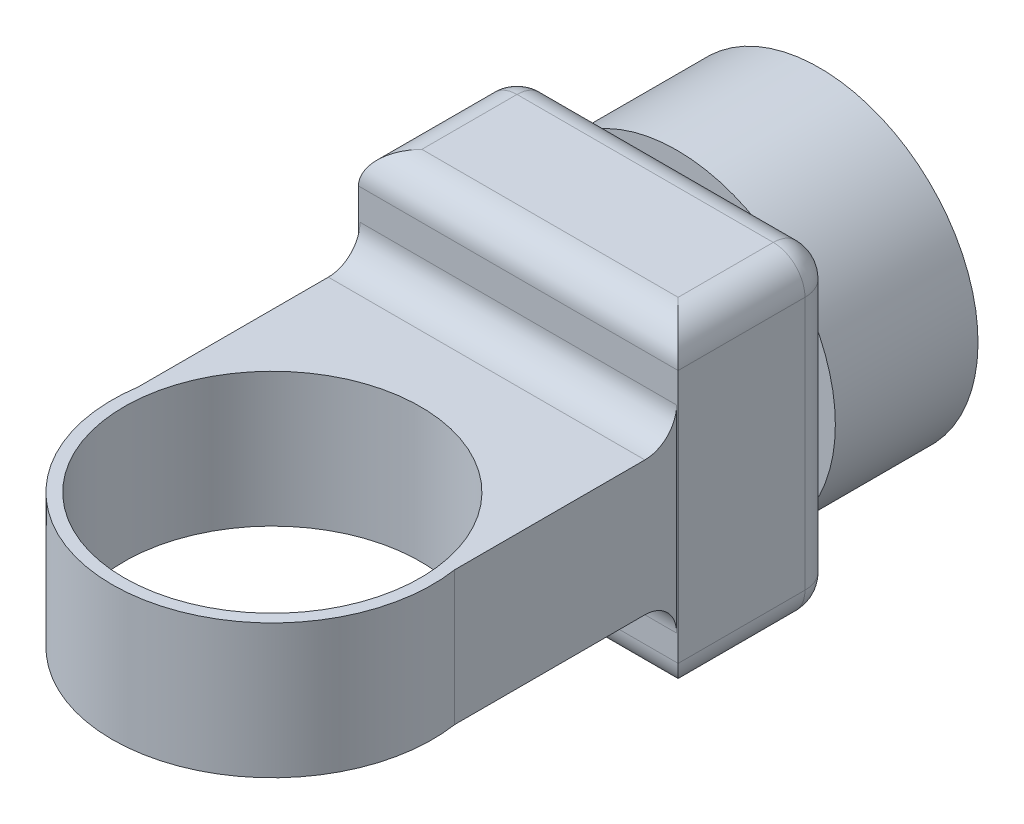
SolidWorks part; units mm, degrees
ref_plane "前视基准面" through (0, 0, 0) normal (0, 0, 1) x (1, 0, 0)
ref_plane "上视基准面" through (0, 0, 0) normal (0, 1, 0) x (1, 0, 0)
ref_plane "右视基准面" through (0, 0, 0) normal (1, 0, 0) x (0, 0, -1)
other "Configuration Table"
sketch "草图1" plane through (0, 0, 0) normal (0, 1, 0) x (1, 0, 0)
  circle A0 centre (0, 0) radius 46.75
  circle A1 centre (0, 0) radius 50.5
  dimension "D1" = 93.5
  dimension "D2" = 101
extrude "凸台-拉伸1" add sketch "草图1" along normal blind 42.3
sketch "草图2" plane through (0, 42.3, 0) normal (0, 1, 0) x (1, 0, 0)
  line L1 (-49.9227, 77.5842) -> (49.9273, 77.5842)
  line L2 (-49.9227, 77.5842) -> (-49.9227, 7.5842)
  line L4 (49.9273, 77.5842) -> (49.9273, 7.5842)
  line L5 (-38.2569, 57.9924) -> (0.0023, 30.5974) construction
  line L6 (-49.9227, 7.5842) -> (0.0023, 30.5974) construction
  circle A0 centre (0, 0) radius 50.5 construction
  arc A4 (-49.9227, 7.5842) -> (49.9273, 7.5842) centre (0.0023, -0.9836) cw
  point P0 (0.0023, 30.5974)
  point P5 (0.0023, 30.5974)
  point P8 (0, 0)
  point P10 (0, 0)
  dimension "D1" = 99.85
  dimension "D2" = 70
  dimension "D3" = 70
extrude "凸台-拉伸3" add sketch "草图2" against normal blind 42.3
sketch "草图10" plane through (0, 0, -77.5842) normal (0, 0, -1) x (-1, 0, 0)
  line L0 (-71.8594, 21.9644) -> (71.8594, 21.9644) construction
  line L1 (0, 92.391) -> (0, -55.3032) construction
  line L3 (-50.415, 71.9644) -> (50.415, 71.9644)
  line L4 (-50.415, 71.9644) -> (-50.415, -28.0356)
  line L5 (-50.415, -28.0356) -> (50.415, -28.0356)
  line L6 (50.415, 71.9644) -> (50.415, -28.0356)
  line L7 (-50.415, 71.9644) -> (50.415, -28.0356) construction
  line L8 (-50.415, -28.0356) -> (50.415, 71.9644) construction
  point P4 (0, 21.9644)
  dimension "D1" = 100
extrude "凸台-拉伸6" add sketch "草图10" along normal blind 50
fillet "圆角13" radius 10 2 edges at (0.0023, 0, -77.5842) (0.0023, 42.3, -77.5842)
fillet "圆角14" radius 10 10 edges at (50.415, -28.0356, -102.5842) (0, -28.0356, -127.5842) (-50.415, -28.0356, -102.5842) (0, -28.0356, -77.5842) (0, 71.9644, -77.5842) (50.415, 71.9644, -102.5842) (0, 71.9644, -127.5842) (-50.415, 71.9644, -102.5842) (50.415, 21.9644, -127.5842) (-50.415, 21.9644, -127.5842)
sketch "草图11" plane through (0, 0, -127.5842) normal (0, 0, -1) x (-1, 0, 0)
  line L0 (-47.4861, 69.0355) -> (47.4861, -25.1067) construction
  line L1 (47.4861, 69.0355) -> (-47.4861, -25.1067) construction
  circle A0 centre (0, 21.9644) radius 50
  arc A1 (-40.415, 71.9644) -> (-50.415, 61.9644) centre (-40.415, 61.9644) ccw construction
  arc A2 (40.415, -28.0356) -> (50.415, -18.0356) centre (40.415, -18.0356) ccw construction
  arc A3 (50.415, 61.9644) -> (40.415, 71.9644) centre (40.415, 61.9644) ccw construction
  arc A4 (-50.415, -18.0356) -> (-40.415, -28.0356) centre (-40.415, -18.0356) ccw construction
  point P18 (0, 21.9644)
  dimension "D1" = 100
extrude "凸台-拉伸7" add sketch "草图11" along normal blind 45
sketch "草图12" plane through (0, 0, -172.5842) normal (0, 0, -1) x (-1, 0, 0)
  line L0 (-47.4861, 69.0355) -> (47.4861, -25.1067) construction
  line L1 (47.4861, 69.0355) -> (-47.4861, -25.1067) construction
  circle A0 centre (0, 21.9644) radius 46.5
  arc A1 (-40.415, 71.9644) -> (-50.415, 61.9644) centre (-40.415, 61.9644) ccw construction
  arc A2 (40.415, -28.0356) -> (50.415, -18.0356) centre (40.415, -18.0356) ccw construction
  arc A3 (50.415, 61.9644) -> (40.415, 71.9644) centre (40.415, 61.9644) ccw construction
  arc A4 (-50.415, -18.0356) -> (-40.415, -28.0356) centre (-40.415, -18.0356) ccw construction
  point P18 (0, 21.9644)
  dimension "D1" = 93
extrude "切除-拉伸1" cut sketch "草图12" against normal blind 42.3
